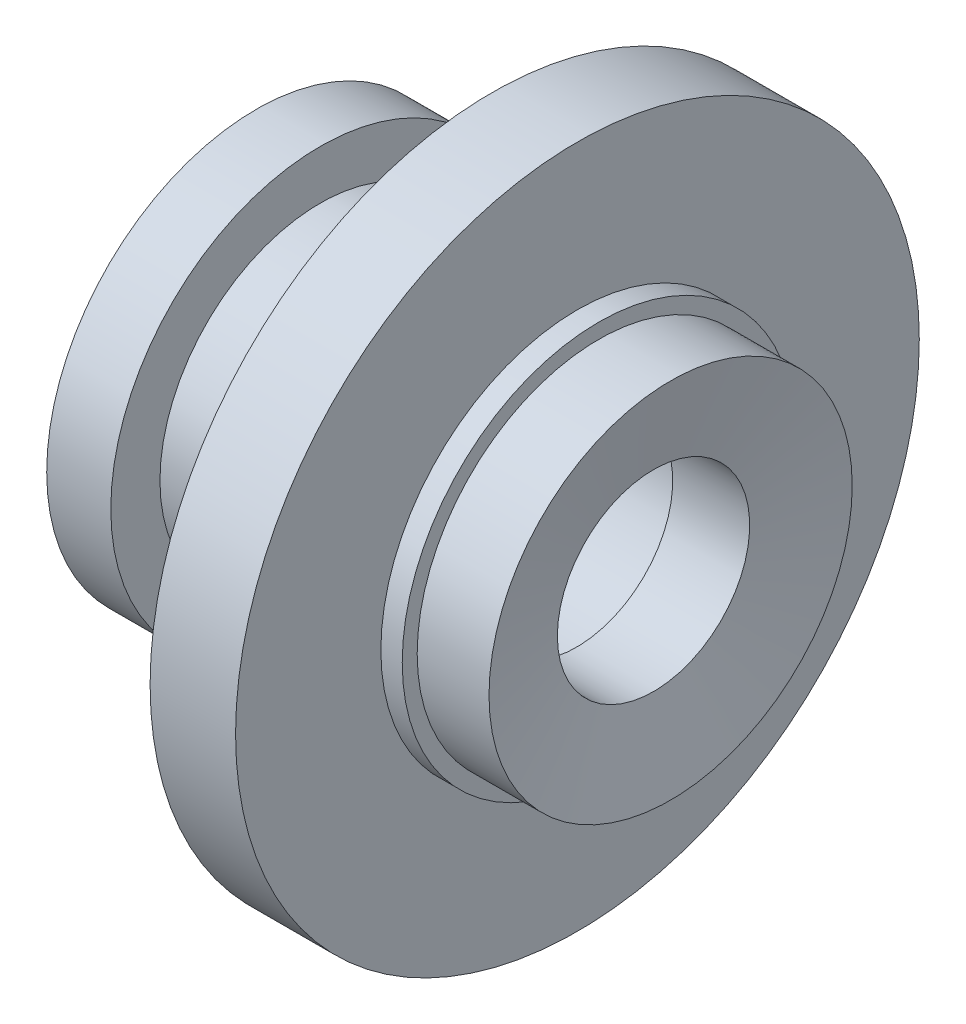
SolidWorks part; units mm, degrees
ref_plane "Front Plane" through (0, 0, 0) normal (0, 0, 1) x (1, 0, 0)
ref_plane "Top Plane" through (0, 0, 0) normal (0, 1, 0) x (1, 0, 0)
ref_plane "Right Plane" through (0, 0, 0) normal (1, 0, 0) x (0, 0, -1)
sketch "Croquis1" plane through (0, 0, 0) normal (0, 0, 1) x (1, 0, 0)
  line L0 (0, 0) -> (75, 0)
  line L1 (75, 0) -> (75, -5)
  line L2 (75, -5) -> (93, -5)
  line L3 (93, -5) -> (97, 15)
  line L4 (97, 15) -> (80.1949, 15)
  line L5 (80.1949, 15) -> (80.1949, 18.5)
  line L6 (80.1949, 18.5) -> (75.1949, 18.5)
  line L7 (75.1949, 18.5) -> (75.1949, 52.5)
  line L8 (75.1949, 52.5) -> (55.1949, 52.5)
  line L9 (55.1949, 52.5) -> (55.1949, 10)
  line L10 (55.1949, 10) -> (15, 10)
  line L11 (15, 10) -> (15, 21.5)
  line L12 (15, 21.5) -> (0, 21.5)
  line L13 (0, 21.5) -> (0, 0)
  line L14 (0, -27.5) -> (97, -27.5) construction
  dimension "D1" = 20
  dimension "D2" = 34
  dimension "D3" = 5
  dimension "D4" = 3.5
  dimension "D5" = 42.5
  dimension "D6" = 11.5
  dimension "D7" = 15
  dimension "D8" = 75
  dimension "D9" = 5
  dimension "D10" = 18
  dimension "D11" = 20
  dimension "D12" = 4
  dimension "D13" = 27.5
revolve "Revolución1" add sketch "Croquis1" angle 360 about L14
